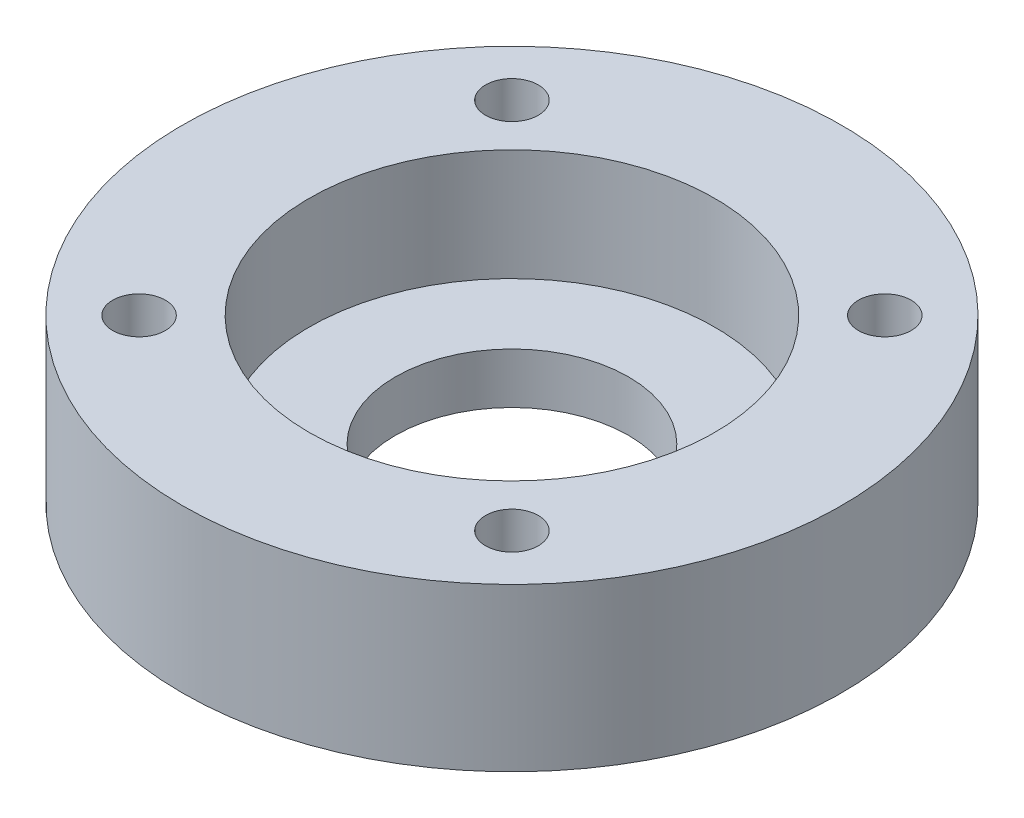
SolidWorks part; units mm, degrees
ref_plane "Front Plane" through (0, 0, 0) normal (0, 0, 1) x (1, 0, 0)
ref_plane "Top Plane" through (0, 0, 0) normal (0, 1, 0) x (1, 0, 0)
ref_plane "Right Plane" through (0, 0, 0) normal (1, 0, 0) x (0, 0, -1)
sketch "Sketch1" plane through (0, 0, 0) normal (0, 1, 0) x (1, 0, 0)
  line L1 (18.3848, -18.3848) -> (-18.3848, -18.3848) construction
  line L2 (18.3848, -18.3848) -> (18.3848, 18.3848) construction
  line L3 (18.3848, 18.3848) -> (-18.3848, 18.3848) construction
  line L4 (-18.3848, -18.3848) -> (-18.3848, 18.3848) construction
  line L5 (18.3848, -18.3848) -> (-18.3848, 18.3848) construction
  line L6 (18.3848, 18.3848) -> (-18.3848, -18.3848) construction
  circle A0 centre (0, 0) radius 11.5
  circle A1 centre (0, 0) radius 20 construction
  circle A2 centre (18.3848, -18.3848) radius 2.6
  circle A3 centre (-18.3848, -18.3848) radius 2.6
  circle A4 centre (-18.3848, 18.3848) radius 2.6
  circle A5 centre (18.3848, 18.3848) radius 2.6
  circle A6 centre (0, 0) radius 32.5
  circle A7 centre (0, 0) radius 26 construction
  dimension "D1" = 23
  dimension "D2" = 40
  dimension "D4" = 5.2
  dimension "D5" = 65
  dimension "D3" = 52
extrude "Boss-Extrude1" add sketch "Sketch1" along normal blind 16
sketch "Sketch2" plane through (0, 16, 0) normal (0, 1, 0) x (1, 0, 0)
  circle A0 centre (0, 0) radius 20
  dimension "D1" = 40
extrude "Cut-Extrude1" cut sketch "Sketch2" against normal blind 11
